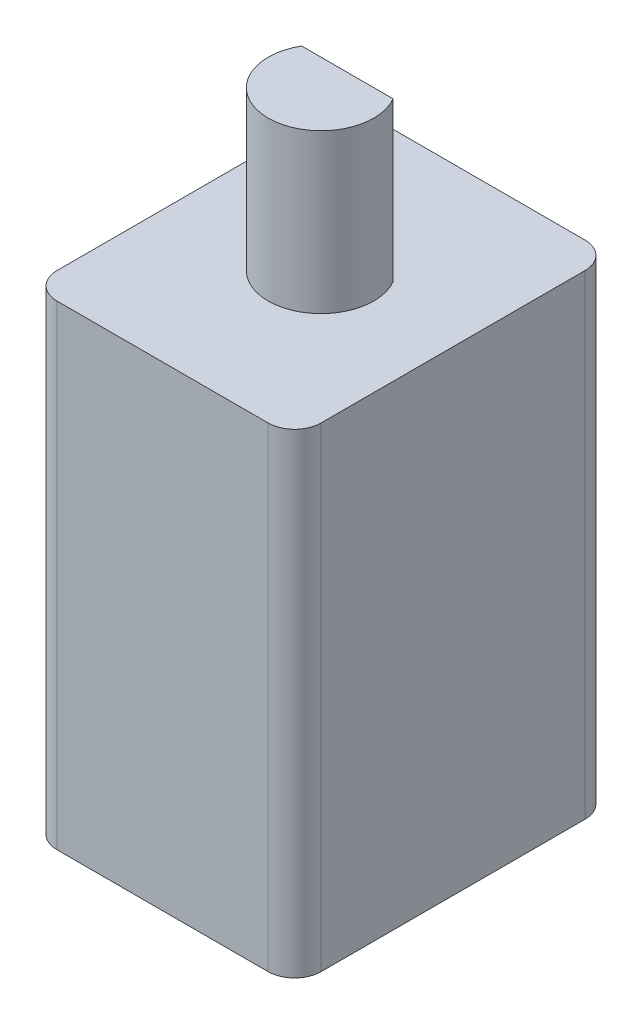
SolidWorks part; units mm, degrees
material "Plástico personalizado"
ref_plane "Alzado" through (0, 0, 0) normal (0, 0, 1) x (1, 0, 0)
ref_plane "Planta" through (0, 0, 0) normal (0, 1, 0) x (1, 0, 0)
ref_plane "Vista lateral" through (0, 0, 0) normal (1, 0, 0) x (0, 0, -1)
sketch "Croquis1" plane through (0, 0, 0) normal (0, 1, 0) x (1, 0, 0)
  line L1 (-5, 6) -> (5, 6)
  line L2 (-5, 6) -> (-5, -6)
  line L3 (-5, -6) -> (5, -6)
  line L4 (5, 6) -> (5, -6)
  line L5 (-5, 6) -> (5, -6) construction
  line L6 (-5, -6) -> (5, 6) construction
  point P0 (0, 0)
  dimension "D1" = 12
  dimension "D2" = 10
extrude "Saliente-Extruir1" add sketch "Croquis1" along normal blind 18
sketch "Croquis2" plane through (0, 18, 0) normal (0, 1, 0) x (1, 0, 0)
  line L0 (-1.7321, 1) -> (1.7321, 1)
  arc A0 (-1.7321, 1) -> (1.7321, 1) centre (0, 0) ccw
  dimension "D1" = 4
  dimension "D2" = 1
extrude "Saliente-Extruir2" add sketch "Croquis2" along normal blind 6
fillet "Redondeo1" radius 1 4 edges at (-5, 9, -6) (5, 9, -6) (-5, 9, 6) (5, 9, 6)
